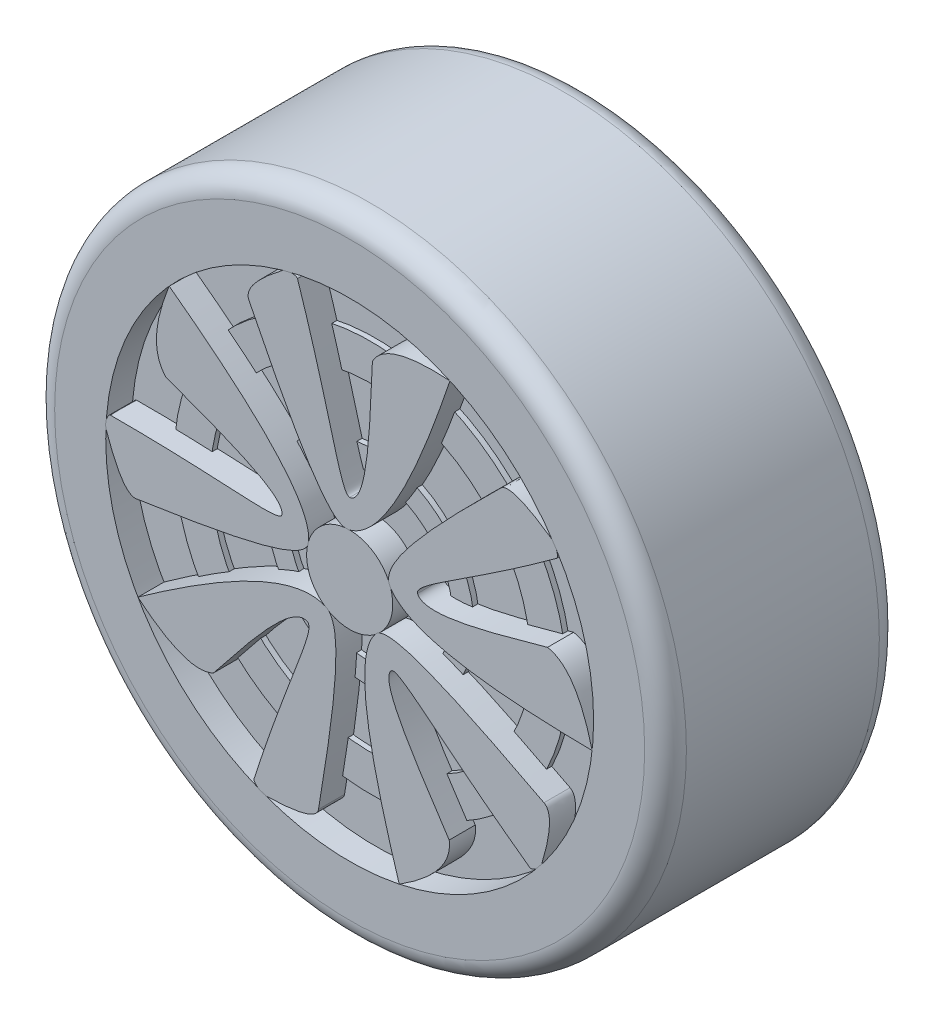
SolidWorks part; units mm, degrees
ref_plane "Front Plane" through (0, 0, 0) normal (0, 0, 1) x (1, 0, 0)
ref_plane "Top Plane" through (0, 0, 0) normal (0, 1, 0) x (1, 0, 0)
ref_plane "Right Plane" through (0, 0, 0) normal (1, 0, 0) x (0, 0, -1)
sketch "Sketch1" plane through (0, 0, 0) normal (0, 0, 1) x (1, 0, 0)
  line L0 (133.6667, 124.5) -> (668.3333, 124.5) construction
  circle A0 centre (136.7012, 61.3776) radius 46.7845
  circle A1 centre (136.7012, 61.3776) radius 60.575
extrude "Boss-Extrude1" add sketch "Sketch1" along normal blind 45
fillet "Fillet1" radius 4 2 edges at (197.2762, 61.3776, 0) (197.2762, 61.3776, 45)
sketch "Sketch7" plane through (0, 0, 45) normal (0, 0, 1) x (1, 0, 0)
  circle A0 centre (136.7012, 61.3776) radius 46.7845 construction
  spline S0 degree 3 poles (155.9335, 104.0263) (151.5246, 90.9634) (144.3253, 71.654) (136.7012, 69.6384) knots 0 0 0 0 1 1 1 1
  spline S1 degree 3 poles (136.7012, 69.6384) (133.2257, 68.3832) (127.3544, 78.0774) (117.3652, 98.1669) knots 0 0 0 0 1 1 1 1
  spline S2 degree 2 poles (117.3652, 98.1669) (116.2492, 100.599) (123.9083, 106.3791) knots 0 0 0 1 1 1
  spline S3 degree 2 poles (155.9335, 104.0263) (143.7321, 104.8404) (141.0623, 99.8493) knots 0 0 0 1 1 1
  spline S4 degree 3 poles (141.0623, 99.8493) (140.6178, 89.8886) (140.277, 75.314) (136.7012, 75.066) knots 0 0 0 0 1 1 1 1
  spline S5 degree 3 poles (136.7012, 75.066) (134.8819, 75.0958) (133.2132, 86.6271) (126.6971, 106.3791) knots 0 0 0 0 1 1 1 1
  spline S6 degree 3 poles (123.9083, 106.3791) (125.0078, 106.9877) (126.5273, 106.7926) (126.6971, 106.3791) knots 0 0 0 0 1 1 1 1
  spline S7 degree 3 poles (183.2057, 56.2658) (169.4196, 56.4223) (148.8307, 57.3023) (144.5577, 63.9303) knots 0 0 0 0 1 1 1 1
  spline S8 degree 3 poles (144.5577, 63.9303) (142.29, 66.848) (149.6954, 75.4275) (165.7148, 91.1358) knots 0 0 0 0 1 1 1 1
  spline S9 degree 2 poles (165.7148, 91.1358) (167.6829, 92.9488) (175.547, 87.4506) knots 0 0 0 1 1 1
  spline S10 degree 2 poles (183.2057, 56.2658) (180.2095, 68.1216) (174.6376, 69.1184) knots 0 0 0 1 1 1
  spline S11 degree 3 poles (174.6376, 69.1184) (165.0271, 66.4632) (151.0605, 62.2834) (149.7197, 65.6076) knots 0 0 0 0 1 1 1 1
  spline S12 degree 3 poles (149.7197, 65.6076) (149.1858, 67.347) (159.6371, 72.4975) (176.4087, 84.7984) knots 0 0 0 0 1 1 1 1
  spline S13 degree 3 poles (175.547, 87.4506) (176.4655, 86.5931) (176.7495, 85.0876) (176.4087, 84.7984) knots 0 0 0 0 1 1 1 1
  spline S14 degree 3 poles (146.2103, 15.5697) (142.099, 28.7293) (136.5736, 48.5825) (141.5568, 54.6945) knots 0 0 0 0 1 1 1 1
  spline S15 degree 3 poles (141.5568, 54.6945) (143.6309, 57.7528) (154.0788, 53.3611) (173.9686, 42.9799) knots 0 0 0 0 1 1 1 1
  spline S16 degree 2 poles (173.9686, 42.9799) (176.301, 41.6683) (173.5021, 32.4902) knots 0 0 0 1 1 1
  spline S17 degree 2 poles (146.2103, 15.5697) (156.56, 22.0828) (155.7861, 27.69) knots 0 0 0 1 1 1
  spline S18 degree 3 poles (155.7861, 27.69) (150.291, 36.0097) (142, 48.0011) (144.7471, 50.3035) knots 0 0 0 0 1 1 1 1
  spline S19 degree 3 poles (144.7471, 50.3035) (146.2364, 51.3487) (154.3645, 43.0006) (171.246, 30.851) knots 0 0 0 0 1 1 1 1
  spline S20 degree 3 poles (173.5021, 32.4902) (172.9704, 31.3515) (171.6264, 30.6162) (171.246, 30.851) knots 0 0 0 0 1 1 1 1
  spline S21 degree 3 poles (96.0738, 38.1785) (107.3189, 46.1552) (124.4929, 57.5451) (131.8457, 54.6945) knots 0 0 0 0 1 1 1 1
  spline S22 degree 3 poles (131.8457, 54.6945) (135.3952, 53.667) (134.4471, 42.3733) (130.7202, 20.249) knots 0 0 0 0 1 1 1 1
  spline S23 degree 2 poles (130.7202, 20.249) (130.1936, 17.6254) (120.5997, 17.4512) knots 0 0 0 1 1 1
  spline S24 degree 2 poles (96.0738, 38.1785) (105.4664, 30.3481) (110.56, 32.8168) knots 0 0 0 1 1 1
  spline S25 degree 3 poles (110.56, 32.8168) (116.7744, 40.6138) (125.6168, 52.2047) (128.6554, 50.3035) knots 0 0 0 0 1 1 1 1
  spline S26 degree 3 poles (128.6554, 50.3035) (130.1097, 49.21) (124.6819, 38.9001) (118.3436, 19.0904) knots 0 0 0 0 1 1 1 1
  spline S27 degree 3 poles (120.5997, 17.4512) (119.3525, 17.605) (118.2379, 18.656) (118.3436, 19.0904) knots 0 0 0 0 1 1 1 1
  spline S28 degree 3 poles (102.083, 92.8477) (113.1442, 84.6179) (129.2838, 71.8041) (128.8448, 63.9303) knots 0 0 0 0 1 1 1 1
  spline S29 degree 3 poles (128.8448, 63.9303) (128.9645, 60.237) (117.9305, 57.6488) (95.7374, 54.3565) knots 0 0 0 0 1 1 1 1
  spline S30 degree 2 poles (95.7374, 54.3565) (93.0795, 54.0466) (89.9491, 63.117) knots 0 0 0 1 1 1
  spline S31 degree 2 poles (102.083, 92.8477) (97.5383, 81.4951) (101.4602, 77.4136) knots 0 0 0 1 1 1
  spline S32 degree 3 poles (101.4602, 77.4136) (110.796, 73.9128) (124.552, 69.085) (123.6828, 65.6076) knots 0 0 0 0 1 1 1 1
  spline S33 degree 3 poles (123.6828, 65.6076) (123.0923, 63.8865) (111.6097, 65.8628) (90.8109, 65.7693) knots 0 0 0 0 1 1 1 1
  spline S34 degree 3 poles (89.9491, 63.117) (89.71, 64.3507) (90.3651, 65.7356) (90.8109, 65.7693) knots 0 0 0 0 1 1 1 1
  point P40 (136.7012, 61.3776)
extrude "Boss-Extrude6" add sketch "Sketch7" against normal blind 5 separate body
sketch "Sketch8" plane through (0, 0, 0) normal (0, 0, 1) x (1, 0, 0)
  circle A0 centre (136.7012, 61.3776) radius 46.7845 construction
  circle A1 centre (136.7012, 61.3776) radius 46.7845
extrude "Boss-Extrude8" add sketch "Sketch8" along normal up to surface (40 mm away) separate body contours A1 up to face at (134.0527, 94.215, 40)
sketch "Sketch9" plane through (0, 0, 0) normal (0, 0, 1) x (1, 0, 0)
  circle A0 centre (136.7012, 61.3776) radius 8.2608
extrude "Boss-Extrude10" add sketch "Sketch9" along normal up to surface (45 mm away) separate body up to face at (134.0527, 94.215, 45)
sketch "Sketch10" plane through (0, 0, 0) normal (0, 0, 1) x (1, 0, 0)
  circle A0 centre (136.7012, 61.3776) radius 15.7135
  circle A1 centre (136.7012, 61.3776) radius 19.8859
  circle A2 centre (136.7012, 61.3776) radius 30.6542
  circle A3 centre (136.7012, 61.3776) radius 37.6214
extrude "Boss-Extrude12" add sketch "Sketch10" along normal blind 41 separate body contours A1 A0 | A3 A2
